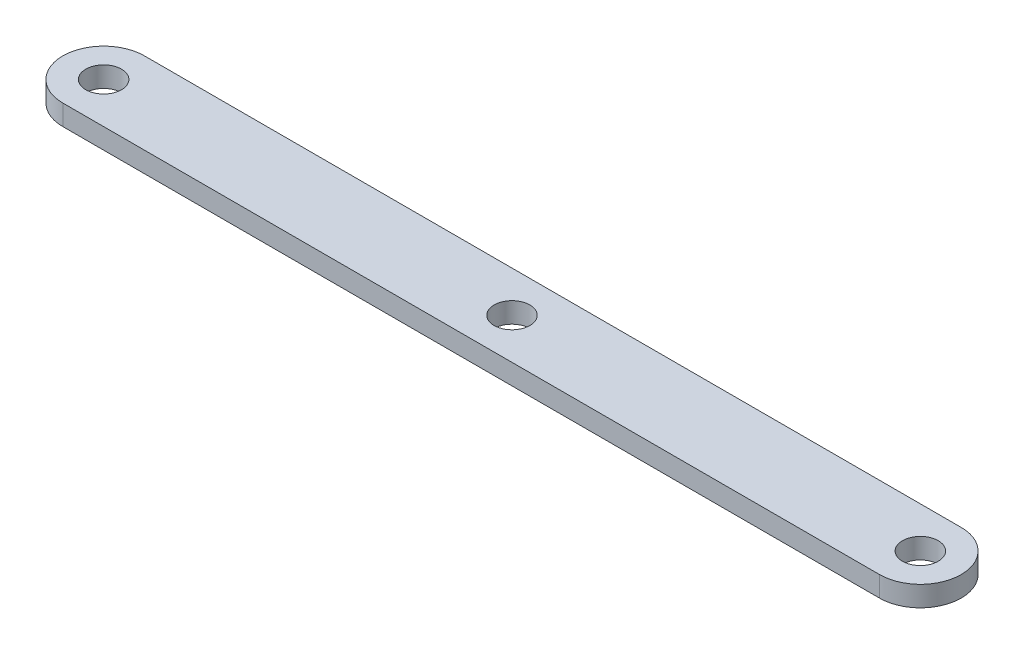
SolidWorks part; units mm, degrees
ref_plane "前视基准面" through (0, 0, 0) normal (0, 0, 1) x (1, 0, 0)
ref_plane "上视基准面" through (0, 0, 0) normal (0, 1, 0) x (1, 0, 0)
ref_plane "右视基准面" through (0, 0, 0) normal (1, 0, 0) x (0, 0, -1)
sketch "草图1" plane through (0, 0, 0) normal (0, 1, 0) x (1, 0, 0)
  line L0 (-52.8566, 0) -> (49.8741, 0) construction
  line L1 (-44.9033, 4) -> (35.0967, 4)
  line L2 (35.0967, -4) -> (-44.9033, -4)
  arc A0 (-44.9033, 4) -> (-44.9033, -4) centre (-44.9033, 0) ccw
  arc A1 (35.0967, -4) -> (35.0967, 4) centre (35.0967, 0) ccw
  dimension "D1" = 8
  dimension "D2" = 8
  dimension "D3" = 80
extrude "凸台-拉伸1" add sketch "草图1" along normal blind 2 contours A0 L2 A1 L1
sketch "草图2" plane through (0, 2, 0) normal (0, 1, 0) x (1, 0, 0)
  line L0 (-48.9033, 0) -> (39.0967, 0) construction
  arc A0 (-44.9033, 4) -> (-44.9033, -4) centre (-44.9033, 0) ccw construction
  arc A1 (35.0967, -4) -> (35.0967, 4) centre (35.0967, 0) ccw construction
  circle A2 centre (-44.9033, 0) radius 1.75
  circle A3 centre (35.0967, 0) radius 1.75
  circle A4 centre (-4.9033, 0) radius 1.75
  dimension "D2" = 3.5
extrude "切除-拉伸1" cut sketch "草图2" against normal through all
